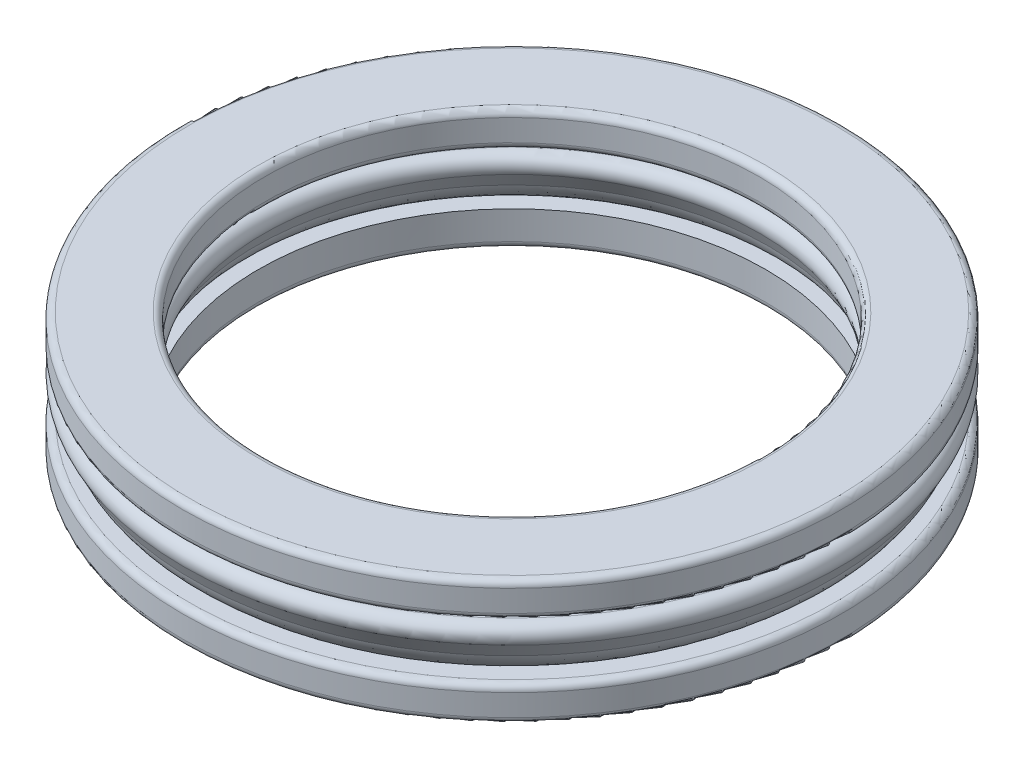
SolidWorks part; units mm, degrees
ref_plane "Front Plane" through (0, 0, 0) normal (0, 0, 1) x (1, 0, 0)
ref_plane "Top Plane" through (0, 0, 0) normal (0, 1, 0) x (1, 0, 0)
ref_plane "Right Plane" through (0, 0, 0) normal (1, 0, 0) x (0, 0, -1)
sketch "Sketch1" plane through (0, 0, 0) normal (0, 0, 1) x (1, 0, 0)
  line L0 (0, 0) -> (0, 19) construction
  line L1 (-41.0741, 13.7) -> (-37.5, 13.7)
  line L2 (-50, 0) -> (-38.5, 0)
  line L3 (-50, 0) -> (-50, 5.3)
  line L4 (-50, 5.3) -> (-46.4259, 5.3)
  line L5 (-38.5, 0) -> (-38.5, 5.3)
  line L6 (-50, 13.7) -> (-46.4259, 13.7)
  line L7 (-50, 13.7) -> (-50, 19)
  line L8 (-50, 19) -> (-37.5, 19)
  line L9 (-37.5, 13.7) -> (-37.5, 19)
  line L10 (-48.3, 12.9) -> (-47.3887, 12.9)
  line L11 (-48.5292, 8.1) -> (-49.7879, 10.3777)
  line L12 (-38.9708, 8.1) -> (-37.7121, 10.3777)
  line L13 (-40.1113, 12.9) -> (-39.2, 12.9)
  line L14 (-41.0741, 5.3) -> (-38.5, 5.3)
  arc A0 (-48.5292, 8.1) -> (-46.4259, 5.3) centre (-43.75, 9.5) ccw
  arc A1 (-37.7121, 10.3777) -> (-39.2, 12.9) centre (-39.2, 11.2) ccw
  arc A2 (-49.7879, 10.3777) -> (-48.3, 12.9) centre (-48.3, 11.2) cw
  arc A3 (-40.1113, 12.9) -> (-41.0741, 13.7) centre (-43.75, 9.5) ccw
  arc A4 (-46.4259, 13.7) -> (-47.3887, 12.9) centre (-43.75, 9.5) ccw
  arc A5 (-41.0741, 5.3) -> (-38.9708, 8.1) centre (-43.75, 9.5) ccw
  dimension "MSM_7" = 9.96
  dimension "MSM_8" = 1.7
  dimension "D1." = 77
  dimension "D_s" = 75
  dimension "D" = 100
  dimension "MSM_5" = 5.3
  dimension "MSM_1" = 13.7
  dimension "T" = 19
  dimension "MSM_3" = 9.5
  dimension "MSM_6" = 87.5
  dimension "MSM_2" = 12.9
  dimension "MSM_4" = 8.1
revolve "Revolve1" add sketch "Sketch1" angle 360 about L0
fillet "Fillet1" radius 1 7 edges at (0, 0, -38.5) (0, 0, -50) (0, 5.3, -50) (0, 13.7, -50) (0, 13.7, -37.5) (0, 19, -37.5) (0, 19, -50)
